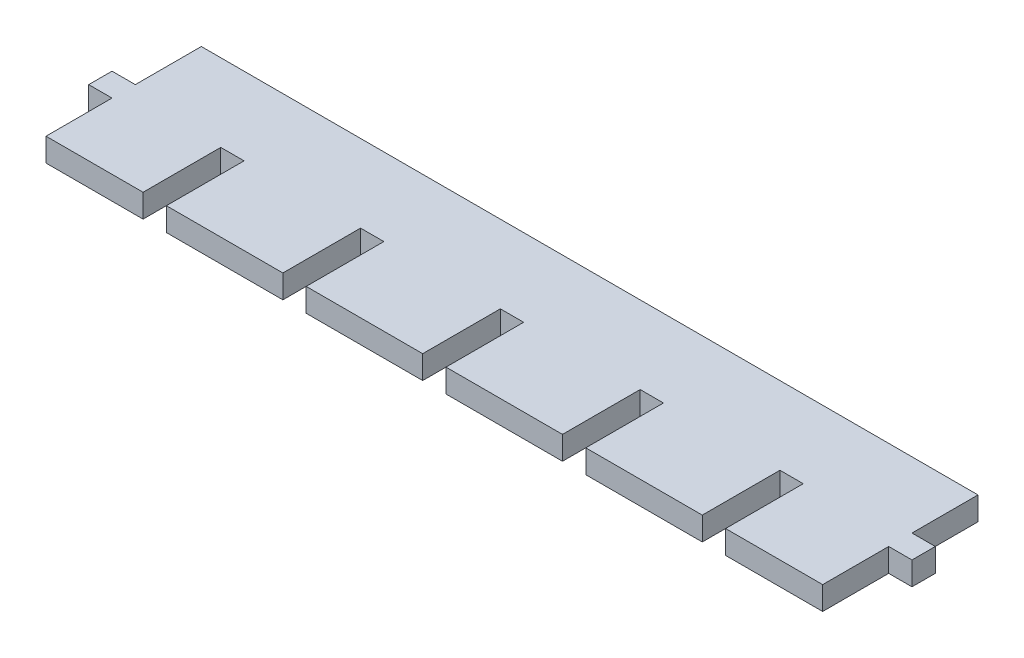
SolidWorks part; units mm, degrees
ref_plane "Front Plane" through (0, 0, 0) normal (0, 0, 1) x (1, 0, 0)
ref_plane "Top Plane" through (0, 0, 0) normal (0, 1, 0) x (1, 0, 0)
ref_plane "Right Plane" through (0, 0, 0) normal (1, 0, 0) x (0, 0, -1)
sketch "Sketch1" plane through (0, 0, 0) normal (0, 1, 0) x (1, 0, 0)
  line L0 (0, 0) -> (-30, 0)
  line L1 (-97, 0) -> (-97, 17)
  line L2 (-97, 40) -> (103, 40)
  line L3 (103, 40) -> (103, 23)
  line L4 (103, 0) -> (78, 0)
  line L5 (78, 0) -> (78, 20)
  line L6 (78, 20) -> (72, 20)
  line L7 (72, 20) -> (72, 0)
  line L8 (42, 0) -> (42, 20)
  line L9 (42, 20) -> (36, 20)
  line L10 (36, 20) -> (36, 0)
  line L11 (72, 0) -> (42, 0)
  line L12 (0, 0) -> (0, 20)
  line L13 (0, 20) -> (6, 20)
  line L14 (6, 20) -> (6, 0)
  line L15 (-36, 0) -> (-36, 20)
  line L16 (-36, 20) -> (-30, 20)
  line L17 (-30, 20) -> (-30, 0)
  line L18 (-72, 0) -> (-72, 20)
  line L19 (-72, 20) -> (-66, 20)
  line L20 (-66, 20) -> (-66, 0)
  line L21 (36, 0) -> (6, 0)
  line L22 (-36, 0) -> (-66, 0)
  line L23 (-72, 0) -> (-97, 0)
  line L24 (-97, 23) -> (-103, 23)
  line L25 (-103, 23) -> (-103, 17)
  line L26 (-103, 17) -> (-97, 17)
  line L27 (-97, 23) -> (-97, 40)
  line L28 (103, 23) -> (109, 23)
  line L29 (109, 23) -> (109, 17)
  line L30 (109, 17) -> (103, 17)
  line L31 (103, 17) -> (103, 0)
  point P16 (6, 10)
  point P25 (-72, 10)
  point P29 (-100, 23)
  point P32 (-100, 17)
  dimension "D1" = 40
  dimension "D2" = 200
  dimension "D3" = 25
  dimension "D4" = 20
  dimension "D5" = 6
  dimension "D6" = 6
  dimension "D7" = 30
  dimension "D8" = 20
  dimension "D9" = 30
  dimension "D10" = 6
  dimension "D11" = 20
  dimension "D12" = 6
  dimension "D13" = 30
  dimension "D14" = 20
  dimension "D15" = 6
  dimension "D16" = 30
  dimension "D17" = 25
  dimension "D18" = 6
  dimension "D19" = 6
  dimension "D20" = 17
  dimension "D21" = 6
  dimension "D22" = 6
  dimension "D23" = 17
extrude "Boss-Extrude1" add sketch "Sketch1" along normal blind 6
